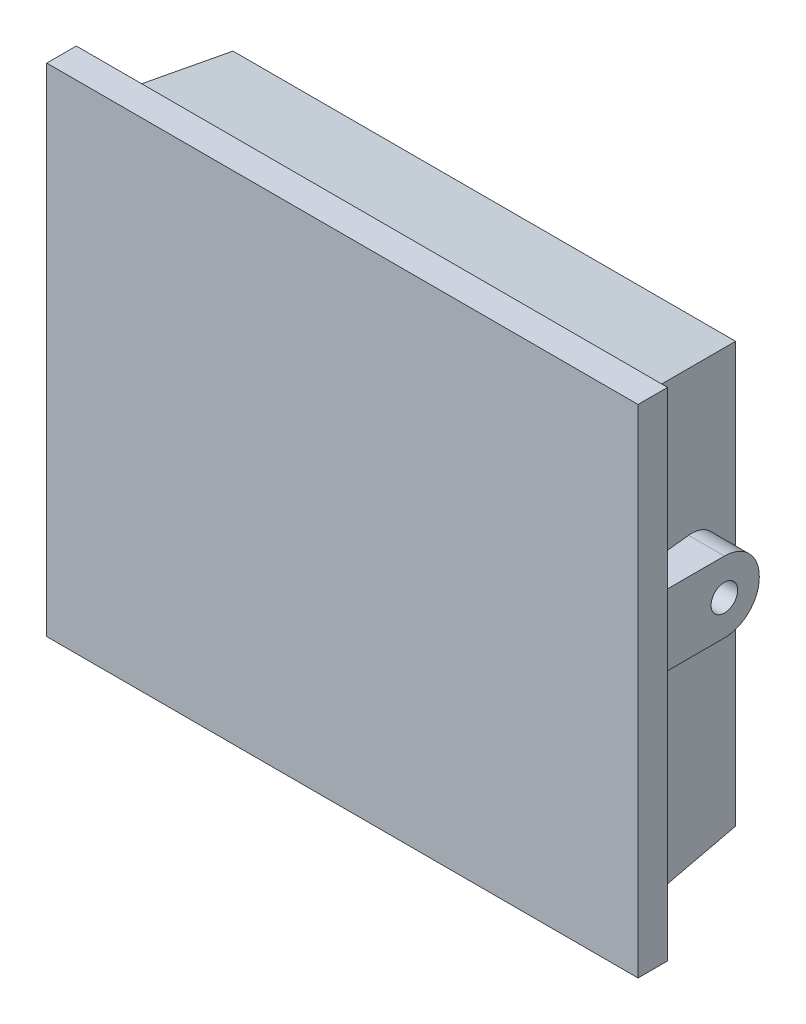
SolidWorks part; units mm, degrees
ref_plane "Alzado" through (0, 0, 0) normal (0, 0, 1) x (1, 0, 0)
ref_plane "Planta" through (0, 0, 0) normal (0, 1, 0) x (1, 0, 0)
ref_plane "Vista lateral" through (0, 0, 0) normal (1, 0, 0) x (0, 0, -1)
sketch "Croquis1" plane through (0, 0, 0) normal (0, 0, 1) x (1, 0, 0)
  line L1 (-50, -42) -> (50, -42)
  line L2 (-50, -42) -> (-50, 42)
  line L3 (-50, 42) -> (50, 42)
  line L4 (50, -42) -> (50, 42)
  line L5 (-50, -42) -> (50, 42) construction
  line L6 (-50, 42) -> (50, -42) construction
  point P0 (0, 0)
  dimension "D1" = 100
  dimension "D2" = 84
extrude "Saliente-Extruir1" add sketch "Croquis1" along normal blind 5
sketch "Croquis2" plane through (0, 0, 0) normal (0, 0, -1) x (-1, 0, 0)
  line L1 (44.5, -37.5) -> (-44.5, -37.5)
  line L2 (44.5, -37.5) -> (44.5, 37.5)
  line L3 (44.5, 37.5) -> (-44.5, 37.5)
  line L4 (-44.5, -37.5) -> (-44.5, 37.5)
  line L5 (44.5, -37.5) -> (-44.5, 37.5) construction
  line L6 (44.5, 37.5) -> (-44.5, -37.5) construction
  point P0 (0, 0)
  dimension "D1" = 89
  dimension "D2" = 75
extrude "Saliente-Extruir2" add sketch "Croquis2" along normal blind 19 draft 6
sketch "Croquis3" plane through (0, 0, 0) normal (1, 0, 0) x (0, 0, -1)
  line L0 (28.7048, 6) -> (-26.5113, 6) construction
  line L1 (0, 37.5) -> (0, -37.5) construction
  line L2 (0, 12) -> (10.1, 12)
  line L3 (0, 12) -> (0, 0)
  line L4 (0, 0) -> (10.1, 0)
  line L5 (16, 6.1) -> (16, 5.9)
  arc A0 (10.1, 0) -> (16, 5.9) centre (10.1, 5.9) ccw
  arc A1 (10.1, 12) -> (16, 6.1) centre (10.1, 6.1) cw
  circle A2 centre (10.1, 5.9) radius 2.25
  point P11 (16, 0)
  point P14 (16, 12)
  dimension "D4" = 5.9
  dimension "D6" = 4.5
  dimension "D1" = 30
  dimension "D2" = 12
  dimension "D3" = 16
  dimension "D5" = 10.1
  dimension "D7" = 6
extrude "Saliente-Extruir3" add sketch "Croquis3" along normal mid plane 99
ref_plane "PlanoGiro" through (0, 6, 0) normal (0, 1, 0) x (1, 0, 0)
